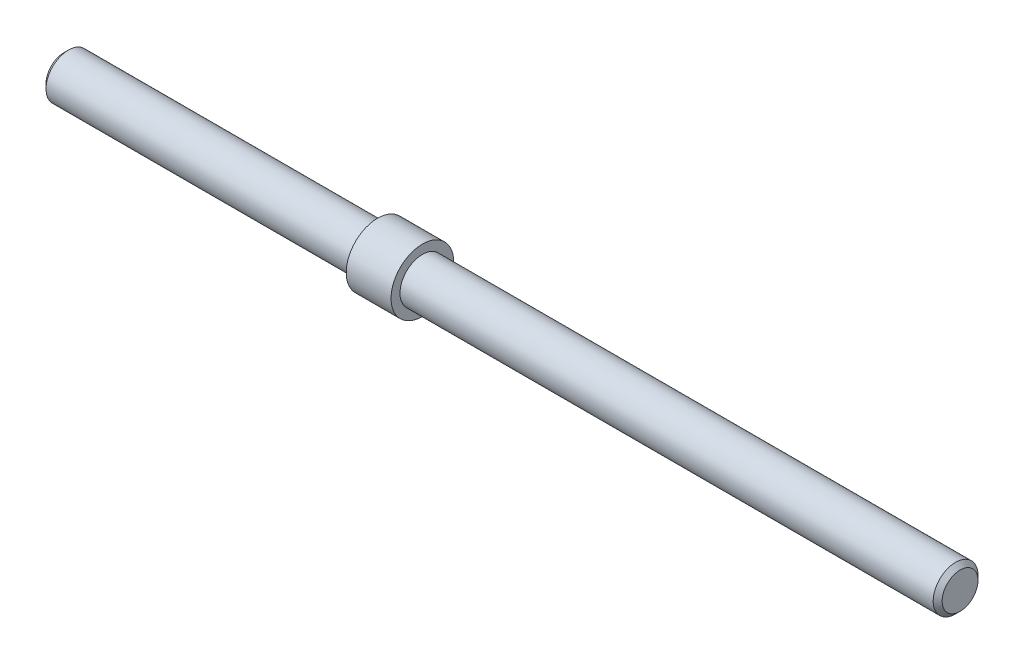
SolidWorks part; units mm, degrees
ref_plane "Front Plane" through (0, 0, 0) normal (0, 0, 1) x (1, 0, 0)
ref_plane "Top Plane" through (0, 0, 0) normal (0, 1, 0) x (1, 0, 0)
ref_plane "Right Plane" through (0, 0, 0) normal (1, 0, 0) x (0, 0, -1)
sketch "Sketch1" plane through (0, 0, 0) normal (1, 0, 0) x (0, 0, -1)
  circle A0 centre (0, 0) radius 5
  dimension "D1" = 5
extrude "Boss-Extrude1" add sketch "Sketch1" along normal blind 200
chamfer "Chamfer1" distance 1 angle 45 2 edges at (200, 0, -5) (0, 0, -5)
sketch "Sketch2" plane through (0, 0, 0) normal (1, 0, 0) x (0, 0, -1)
  circle A1 centre (0, 0) radius 7
  dimension "D1" = 14
extrude "Boss-Extrude2" add sketch "Sketch2" along normal blind 10 from offset 70
